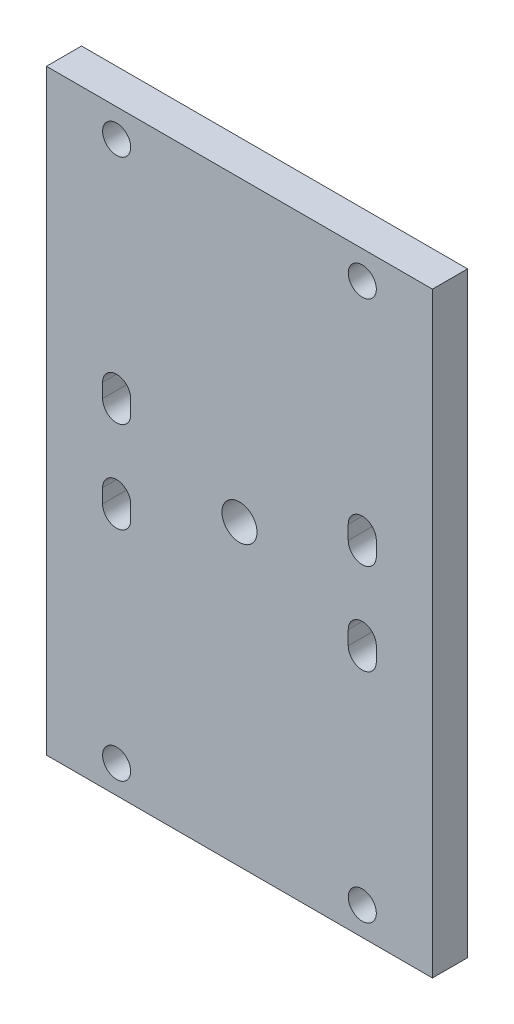
SolidWorks part; units mm, degrees
ref_plane "Plan de face" through (0, 0, 0) normal (0, 0, 1) x (1, 0, 0)
ref_plane "Plan de dessus" through (0, 0, 0) normal (0, 1, 0) x (1, 0, 0)
ref_plane "Plan de droite" through (0, 0, 0) normal (1, 0, 0) x (0, 0, -1)
sketch "Esquisse1" plane through (0, 0, 0) normal (0, 0, 1) x (1, 0, 0)
  line L1 (-27.5, -42.5) -> (27.5, -42.5)
  line L2 (-27.5, -42.5) -> (-27.5, 42.5)
  line L3 (-27.5, 42.5) -> (27.5, 42.5)
  line L4 (27.5, -42.5) -> (27.5, 42.5)
  line L5 (-27.5, -42.5) -> (27.5, 42.5) construction
  line L6 (-27.5, 42.5) -> (27.5, -42.5) construction
  point P0 (0, 0)
  dimension "D1" = 55
  dimension "D2" = 85
extrude "Boss.-Extru.1" add sketch "Esquisse1" along normal blind 5
sketch "Sketch1" plane through (0, 0, 5) normal (0, 0, 1) x (1, 0, 0)
  line L0 (-27.5, 0) -> (-18.2602, 0) construction
  line L1 (-27.5, 42.5) -> (-27.5, -42.5) construction
  line L2 (27.5, 42.5) -> (-27.5, 42.5) construction
  line L4 (0, 42.5) -> (0, 30.9604) construction
  line L5 (0, -42.5) -> (0, -30.9604) construction
  circle A0 centre (-17.5, 38.5) radius 2
  circle A1 centre (-17.5, 7.5) radius 2
  circle A2 centre (17.5, 7.5) radius 2
  circle A3 centre (17.5, 38.5) radius 2
  circle A4 centre (17.5, -38.5) radius 2
  circle A5 centre (17.5, -7.5) radius 2
  circle A6 centre (-17.5, -7.5) radius 2
  circle A7 centre (-17.5, -38.5) radius 2
  point P15 (0, 0)
  dimension "D1" = 4
  dimension "D2" = 4
  dimension "D3" = 4
  dimension "D4" = 15
  dimension "D6" = 17.5
extrude "Cut-Extrude1" cut sketch "Sketch1" against normal blind 10
sketch "Sketch2" plane through (0, 0, 0) normal (0, 0, -1) x (-1, 0, 0)
  line L0 (-19.5, 7.5) -> (-19.5, 5.5)
  line L1 (-15.5, 7.5) -> (-15.5, 5.5)
  line L2 (0, 0) -> (-3.7615, 0) construction
  line L3 (-3.7615, 0) -> (0, 0) construction
  line L4 (0, 4.3493) -> (0, 0) construction
  line L5 (15.5, 7.5) -> (15.5, 5.5)
  line L6 (19.5, 7.5) -> (19.5, 5.5)
  line L7 (19.5, -7.5) -> (19.5, -5.5)
  line L8 (15.5, -7.5) -> (15.5, -5.5)
  line L9 (-15.5, -7.5) -> (-15.5, -5.5)
  line L10 (-19.5, -7.5) -> (-19.5, -5.5)
  circle A0 centre (-17.5, 7.5) radius 2 construction
  arc A1 (-15.5, 7.5) -> (-19.5, 7.5) centre (-17.5, 7.5) ccw
  arc A2 (-19.5, 5.5) -> (-15.5, 5.5) centre (-17.5, 5.5) ccw
  arc A3 (19.5, 5.5) -> (15.5, 5.5) centre (17.5, 5.5) cw
  arc A4 (15.5, 7.5) -> (19.5, 7.5) centre (17.5, 7.5) cw
  arc A5 (15.5, -7.5) -> (19.5, -7.5) centre (17.5, -7.5) ccw
  arc A6 (19.5, -5.5) -> (15.5, -5.5) centre (17.5, -5.5) ccw
  arc A7 (-19.5, -5.5) -> (-15.5, -5.5) centre (-17.5, -5.5) cw
  arc A8 (-15.5, -7.5) -> (-19.5, -7.5) centre (-17.5, -7.5) cw
extrude "Cut-Extrude2" cut sketch "Sketch2" against normal blind 10
sketch "Sketch3" plane through (0, 0, 5) normal (0, 0, 1) x (1, 0, 0)
  circle A0 centre (0, 0) radius 2.5
  dimension "D1" = 5
extrude "Cut-Extrude3" cut sketch "Sketch3" against normal blind 10
